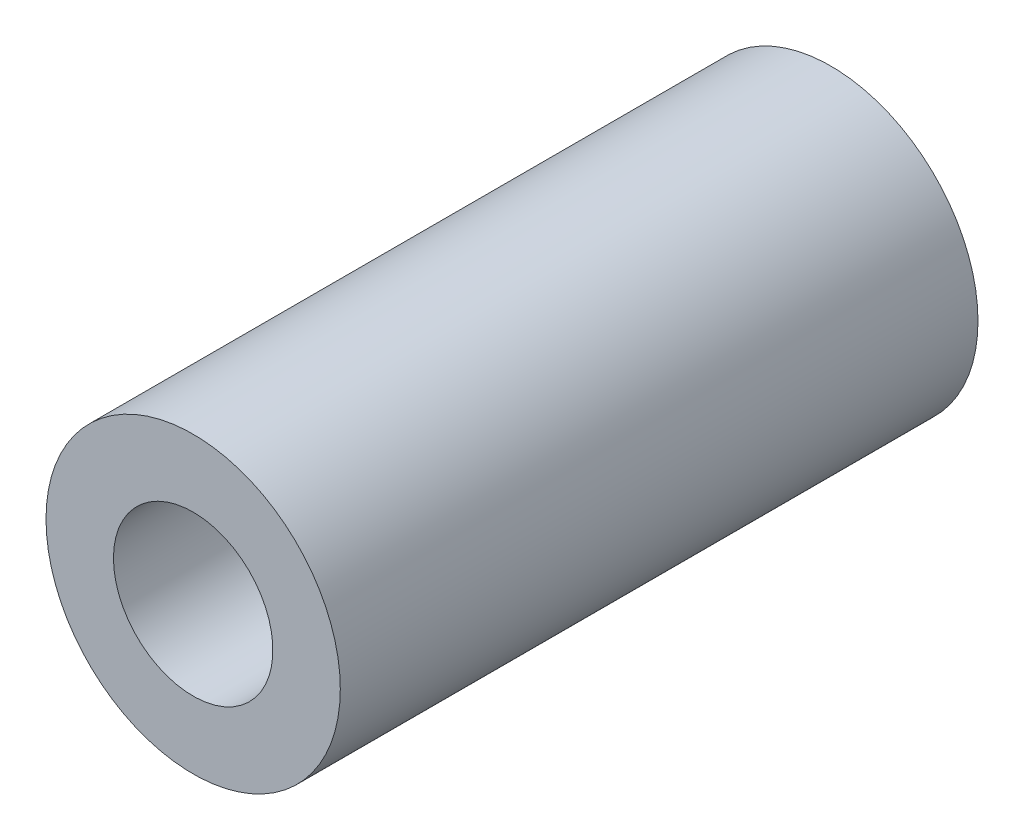
SolidWorks part; units mm, degrees
ref_plane "Alzado" through (0, 0, 0) normal (0, 0, 1) x (1, 0, 0)
ref_plane "Planta" through (0, 0, 0) normal (0, 1, 0) x (1, 0, 0)
ref_plane "Vista lateral" through (0, 0, 0) normal (1, 0, 0) x (0, 0, -1)
sketch "Croquis1" plane through (0, 0, 0) normal (0, 0, 1) x (1, 0, 0)
  circle A0 centre (0, 0) radius 3.25
  circle A1 centre (0, 0) radius 6
  dimension "D1" = 6.5
  dimension "D2" = 12
extrude "Saliente-Extruir1" add sketch "Croquis1" along normal blind 26
